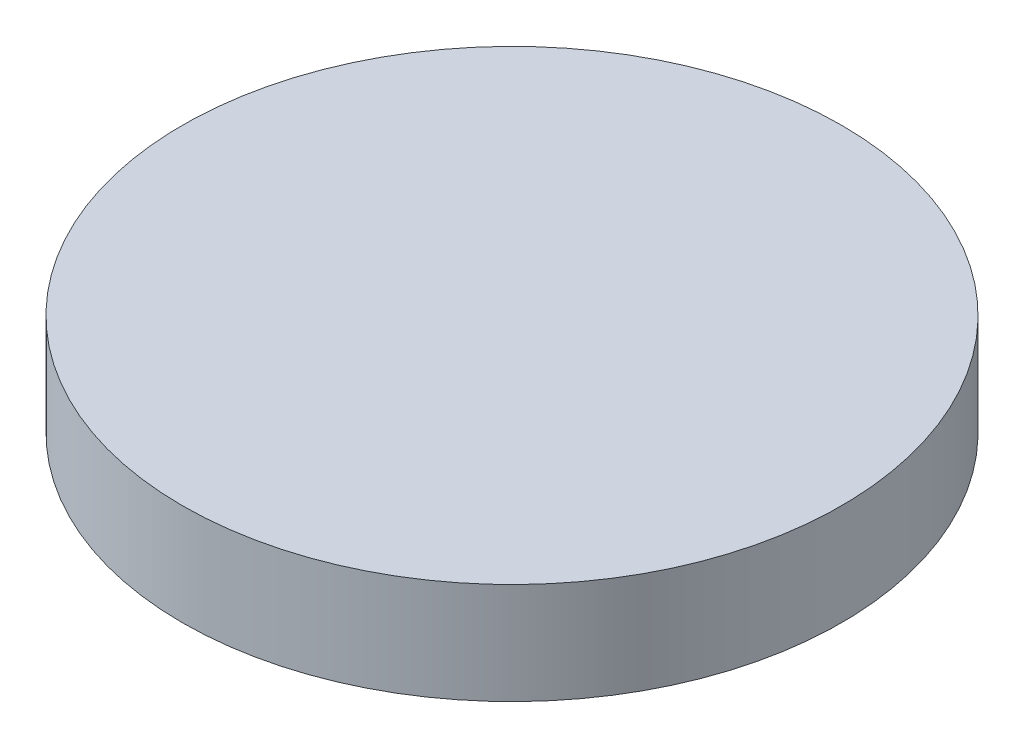
SolidWorks part; units mm, degrees
ref_plane "Front Plane" through (0, 0, 0) normal (0, 0, 1) x (1, 0, 0)
ref_plane "Top Plane" through (0, 0, 0) normal (0, 1, 0) x (1, 0, 0)
ref_plane "Right Plane" through (0, 0, 0) normal (1, 0, 0) x (0, 0, -1)
sketch "Sketch1" plane through (0, 0, 0) normal (0, 1, 0) x (1, 0, 0)
  circle A0 centre (0, 0) radius 20.64
  dimension "D1" = 41.28
extrude "Boss-Extrude1" add sketch "Sketch1" along normal blind 6.35
